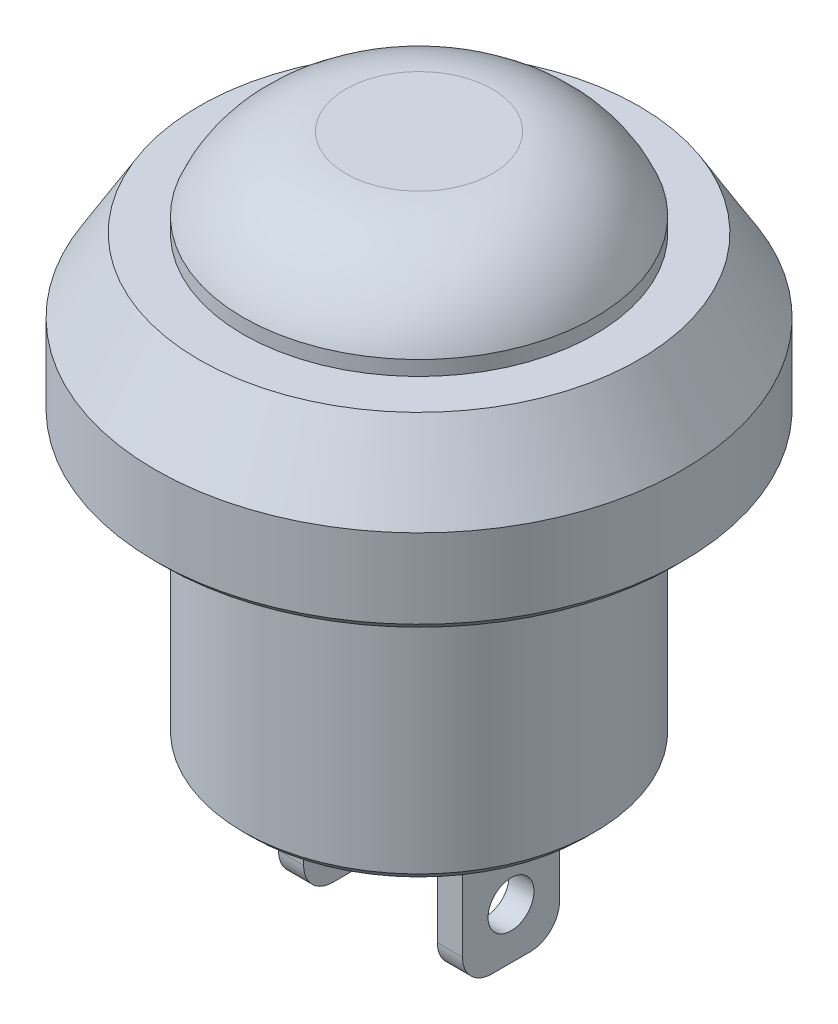
SolidWorks part; units mm, degrees
ref_plane "Front Plane" through (0, 0, 0) normal (0, 0, 1) x (1, 0, 0)
ref_plane "Top Plane" through (0, 0, 0) normal (0, 1, 0) x (1, 0, 0)
ref_plane "Right Plane" through (0, 0, 0) normal (1, 0, 0) x (0, 0, -1)
sketch "Sketch1" plane through (0, 0, 0) normal (0, 0, 1) x (1, 0, 0)
  line L0 (0, 0) -> (0, -27.386) construction
  line L1 (0, 0) -> (2.5, 0)
  line L2 (6, -2.5) -> (6, -3)
  line L3 (6, -3) -> (7.5, -3)
  line L4 (7.5, -3) -> (9, -5.5)
  line L5 (9, -5.5) -> (9, -8.5)
  line L6 (9, -8.5) -> (6, -8.5)
  line L7 (6, -8.5) -> (6, -18)
  line L8 (6, -18) -> (0, -18)
  line L9 (0, 0) -> (0, -18)
  arc A0 (6, -2.5) -> (2.5, 0) centre (2.2897, -3.9945) ccw
  dimension "D11" = 4
  dimension "D1" = 12
  dimension "D2" = 18
  dimension "D3" = 5.5
  dimension "D5" = 18
  dimension "D6" = 12
  dimension "D7" = 1.5
  dimension "D8" = 2.5
  dimension "D9" = 0.5
  dimension "D10" = 2.5
revolve "Revolve1" add sketch "Sketch1" angle 360 about L0
chamfer "Chamfer1" distance 0.3 angle 45 3 edges at (0, -18, 6) (0, -8.5, 6) (0, -8.5, 9)
sketch "Sketch2" plane through (0, -18, 0) normal (0, -1, 0) x (1, 0, 0)
  line L0 (0, 9.4642) -> (0, 0) construction
  line L1 (-2.2814, 1.6576) -> (-3.1369, -1.6576) construction
  line L2 (2.2814, -1.6576) -> (3.1369, -1.6576)
  line L3 (2.2814, -1.6576) -> (2.2814, 1.6576)
  line L4 (2.2814, 1.6576) -> (3.1369, 1.6576)
  line L5 (3.1369, -1.6576) -> (3.1369, 1.6576)
  line L6 (2.2814, -1.6576) -> (3.1369, 1.6576) construction
  line L7 (2.2814, 1.6576) -> (3.1369, -1.6576) construction
  line L8 (-2.2814, -1.6576) -> (-3.1369, 1.6576) construction
  line L9 (-3.1369, -1.6576) -> (-3.1369, 1.6576)
  line L10 (-2.2814, 1.6576) -> (-3.1369, 1.6576)
  line L11 (-2.2814, -1.6576) -> (-2.2814, 1.6576)
  line L12 (-2.2814, -1.6576) -> (-3.1369, -1.6576)
  point P3 (2.7092, 0)
  point P12 (-2.7092, 0)
extrude "Boss-Extrude1" add sketch "Sketch2" along normal blind 5
sketch "Sketch3" plane through (-3.1369, 0, 0) normal (-1, 0, 0) x (0, 0, 1)
  circle A0 centre (0, -21.2702) radius 0.7836
extrude "Cut-Extrude1" cut sketch "Sketch3" against normal blind 12
fillet "Fillet1" radius 1 4 edges at (-2.7092, -23, -1.6576) (-2.7092, -23, 1.6576) (2.7092, -23, 1.6576) (2.7092, -23, -1.6576)
